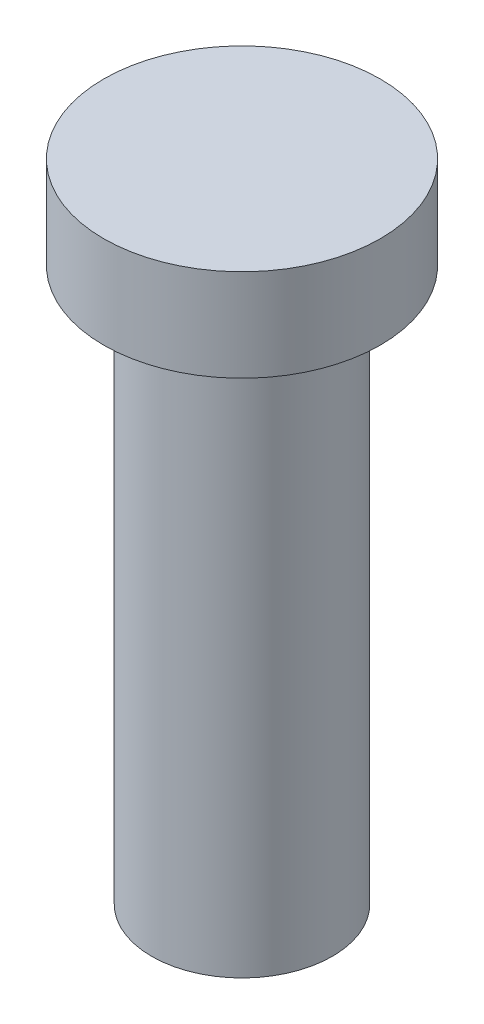
SolidWorks part; units mm, degrees
ref_plane "Front Plane" through (0, 0, 0) normal (0, 0, 1) x (1, 0, 0)
ref_plane "Top Plane" through (0, 0, 0) normal (0, 1, 0) x (1, 0, 0)
ref_plane "Right Plane" through (0, 0, 0) normal (1, 0, 0) x (0, 0, -1)
sketch "Sketch1" plane through (0, 0, 0) normal (0, 1, 0) x (1, 0, 0)
  circle A0 centre (0, 0) radius 9.8
extrude "Boss-Extrude1" add sketch "Sketch1" along normal blind 60
sketch "Sketch2" plane through (0, 60, 0) normal (0, 1, 0) x (1, 0, 0)
  circle A0 centre (0, 0) radius 15
extrude "Boss-Extrude2" add sketch "Sketch2" along normal blind 10
